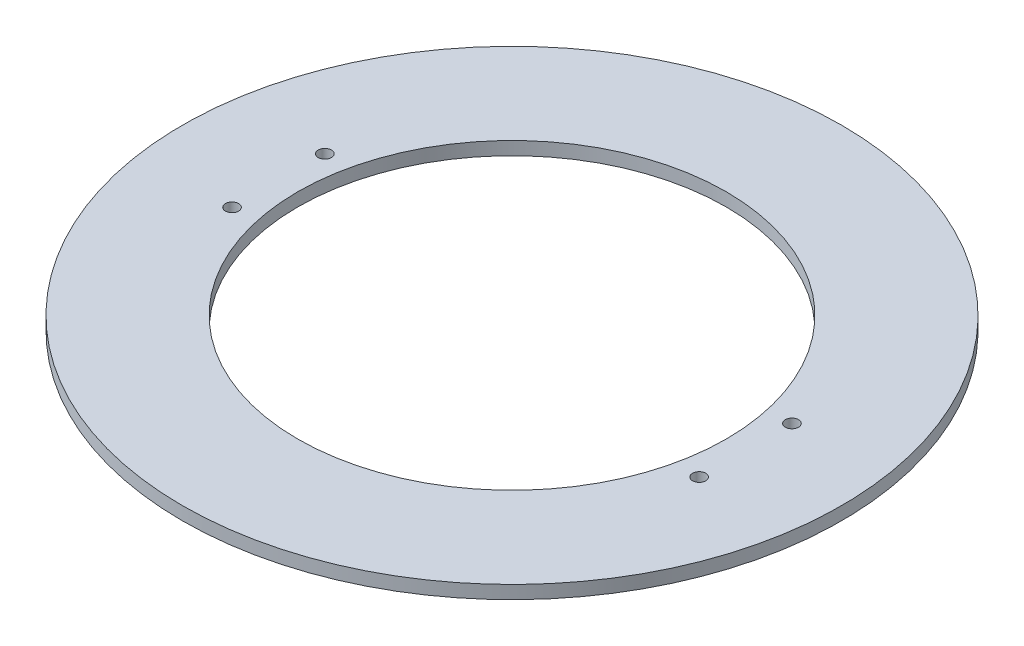
SolidWorks part; units mm, degrees
material "6061-T6 (SS)"
ref_plane "Front Plane" through (0, 0, 0) normal (0, 0, 1) x (1, 0, 0)
ref_plane "Top Plane" through (0, 0, 0) normal (0, 1, 0) x (1, 0, 0)
ref_plane "Right Plane" through (0, 0, 0) normal (1, 0, 0) x (0, 0, -1)
sketch "Sketch2" plane through (0, 0, 0) normal (0, 1, 0) x (1, 0, 0)
  line L0 (-100, 0) -> (100, 0) construction
  line L1 (-70.87, 70.551) -> (-70.87, -70.551) construction
  line L2 (0, 100) -> (0, -100) construction
  line L3 (70.87, 70.551) -> (70.87, -70.551) construction
  circle A0 centre (0, 0) radius 65
  circle A1 centre (0, 0) radius 100
  circle A2 centre (-70.87, 14.075) radius 2
  circle A3 centre (-70.87, -14.075) radius 2
  circle A4 centre (70.87, -14.075) radius 2
  circle A5 centre (70.87, 14.075) radius 2
  dimension "D1" = 130
  dimension "D2" = 200
  dimension "D3" = 4
  dimension "D5" = 28.15
  dimension "D4" = 141.74
extrude "Boss-Extrude1" add sketch "Sketch2" along normal blind 4
sketch "Sketch3" plane through (0, 4, 0) normal (0, 1, 0) x (1, 0, 0)
  line L0 (0, 100) -> (0, 65) construction
  circle A0 centre (0, 0) radius 82.5 construction
  circle A1 centre (0, 0) radius 100 construction
  circle A2 centre (0, 0) radius 65 construction
  point P10 (0, 82.5)
